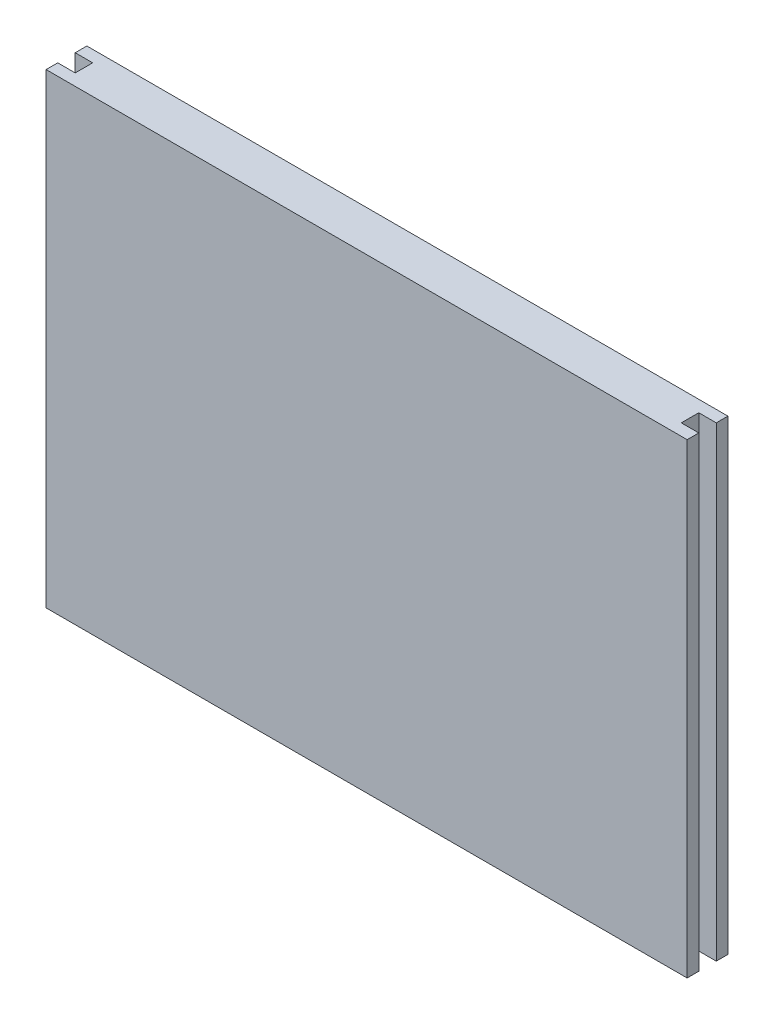
SolidWorks part; units mm, degrees
ref_plane "Front Plane" through (0, 0, 0) normal (0, 0, 1) x (1, 0, 0)
ref_plane "Top Plane" through (0, 0, 0) normal (0, 1, 0) x (1, 0, 0)
ref_plane "Right Plane" through (0, 0, 0) normal (1, 0, 0) x (0, 0, -1)
sketch "Sketch1" plane through (0, 0, 0) normal (0, 1, 0) x (1, 0, 0)
  line L0 (0, 0) -> (-110, 0)
  line L1 (-110, 0) -> (-110, 2)
  line L2 (-110, 2) -> (-107, 2)
  line L3 (-107, 2) -> (-107, 5)
  line L4 (-107, 5) -> (-110, 5)
  line L5 (-110, 5) -> (-110, 7)
  line L6 (-110, 7) -> (0, 7)
  line L7 (0, 7) -> (0, 5)
  line L8 (0, 5) -> (-3, 5)
  line L9 (-3, 5) -> (-3, 2)
  line L10 (-3, 2) -> (0, 2)
  line L11 (0, 2) -> (0, 0)
  dimension "D1" = 110
  dimension "D2" = 2
  dimension "D3" = 2
  dimension "D4" = 2
  dimension "D5" = 2
  dimension "D6" = 3
  dimension "D7" = 3
  dimension "D8" = 3
  dimension "D9" = 3
extrude "Boss-Extrude1" add sketch "Sketch1" along normal blind 80
